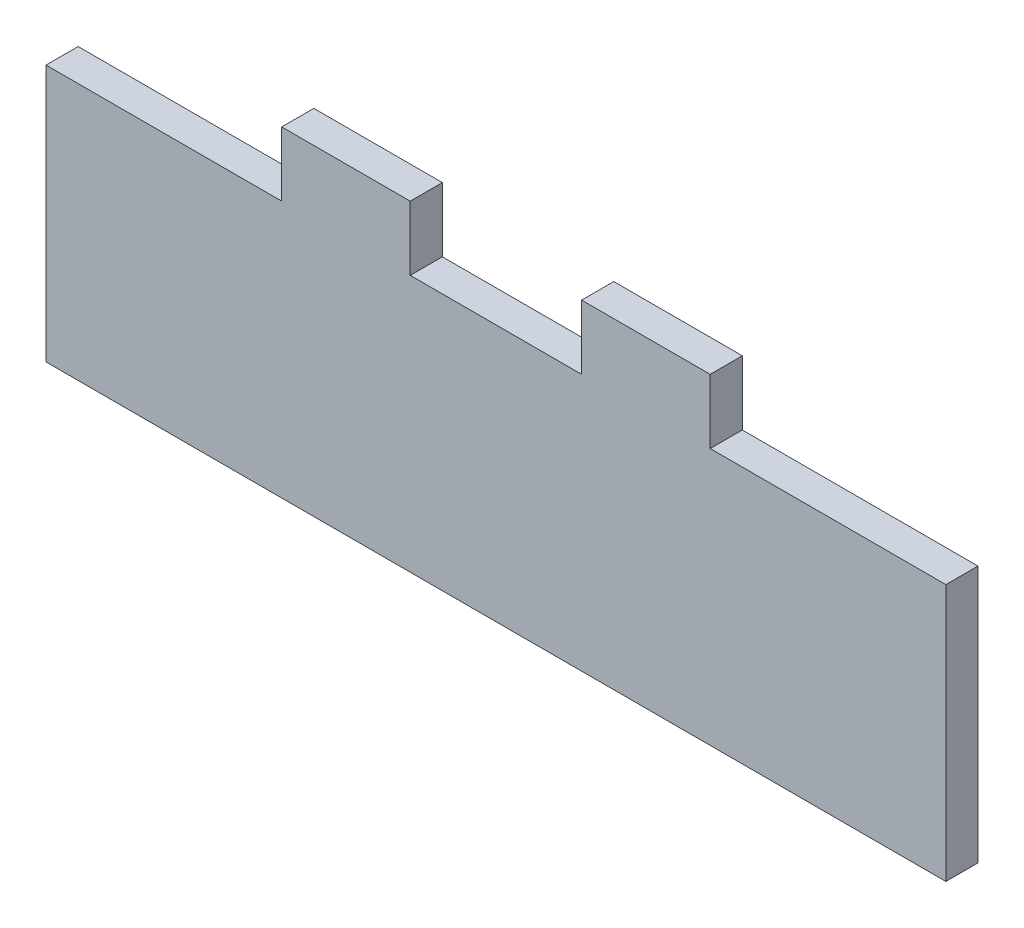
SolidWorks part; units mm, degrees
ref_plane "Front Plane" through (0, 0, 0) normal (0, 0, 1) x (1, 0, 0)
ref_plane "Top Plane" through (0, 0, 0) normal (0, 1, 0) x (1, 0, 0)
ref_plane "Right Plane" through (0, 0, 0) normal (1, 0, 0) x (0, 0, -1)
sketch "Sketch1" plane through (0, 0, 0) normal (0, 0, 1) x (1, 0, 0)
  line L0 (35, 21.9771) -> (-35, 21.9771) construction
  line L1 (35, 10) -> (-35, 10)
  line L2 (35, 10) -> (35, -10)
  line L3 (35, -10) -> (-35, -10)
  line L4 (-35, 10) -> (-35, -10)
  line L5 (35, 10) -> (-35, -10) construction
  line L6 (35, -10) -> (-35, 10) construction
  line L16 (-16.6667, 10) -> (-6.6667, 10)
  line L17 (-16.6667, 10) -> (-16.6667, 15)
  line L18 (-16.6667, 15) -> (-6.6667, 15)
  line L19 (-6.6667, 10) -> (-6.6667, 15)
  line L20 (6.6667, 10) -> (16.6667, 10)
  line L21 (6.6667, 10) -> (6.6667, 15)
  line L22 (6.6667, 15) -> (16.6667, 15)
  line L23 (16.6667, 10) -> (16.6667, 15)
  point P0 (0, 0)
  point P14 (11.6667, 21.9771)
  point P15 (-11.6667, 21.9771)
  point P17 (-11.6667, 15)
  point P20 (0, 21.9771)
  point P22 (11.6667, 15)
  dimension "D1" = 70
  dimension "D4" = 20
  dimension "D5" = 70
  dimension "D2" = 5
  dimension "D3" = 10
extrude "Boss-Extrude1" add sketch "Sketch1" along normal blind 2.5
equation "\"thick5mm\" = 5mm"
equation "\"D1@Boss-Extrude1\" = \"thick2.5mm\""
equation "\"D2@Sketch1\"= \"thick5mm\""
equation "\"thick2.5mm\"= 2.5mm"
